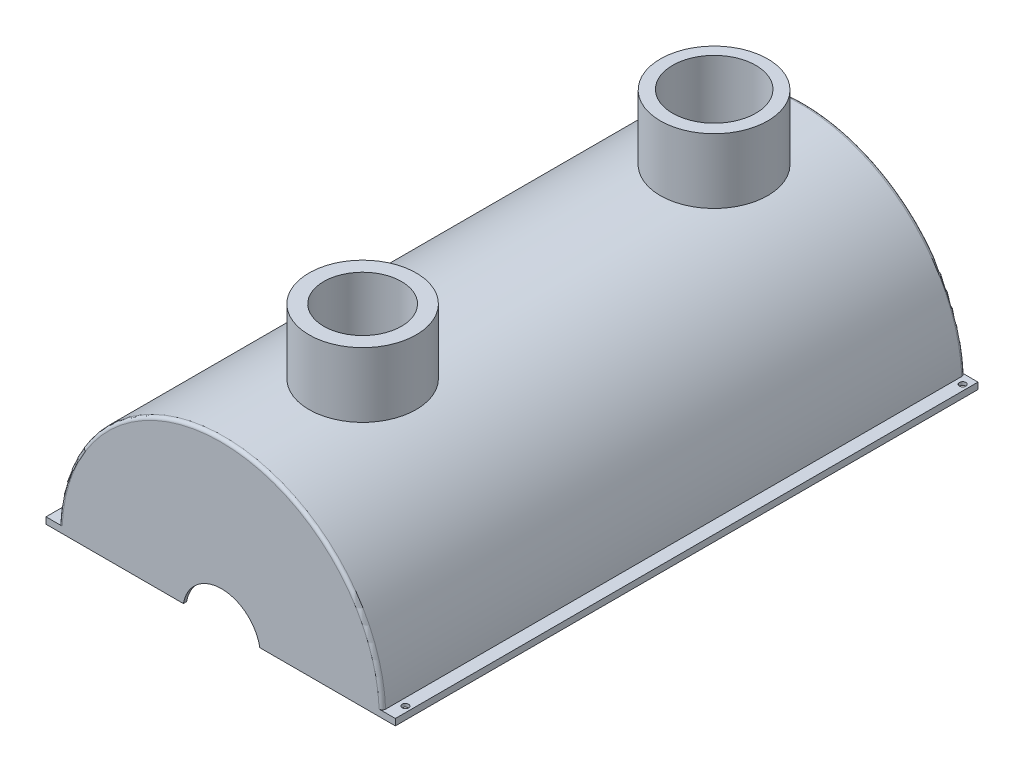
SolidWorks part; units mm, degrees
ref_plane "Front Plane" through (0, 0, 0) normal (0, 0, 1) x (1, 0, 0)
ref_plane "Top Plane" through (0, 0, 0) normal (0, 1, 0) x (1, 0, 0)
ref_plane "Right Plane" through (0, 0, 0) normal (1, 0, 0) x (0, 0, -1)
sketch "Sketch1" plane through (0, 0, 0) normal (0, 0, 1) x (1, 0, 0)
  line L0 (0, 0) -> (384.7575, 0)
  line L1 (620.9318, 0) -> (1000, 0)
  arc A0 (1000, 0) -> (0, 0) centre (500, 0) ccw
  arc A1 (384.7575, 0) -> (620.9318, 0) centre (502.8446, -21.3409) cw
  dimension "D2" = 120
  dimension "D1" = 1000
extrude "Boss-Extrude1" add sketch "Sketch1" along normal blind 1800
sketch "Sketch2" plane through (0, 0, 0) normal (0, 0, 1) x (1, 0, 0)
  line L0 (1000, 0) -> (1039.5998, 0)
  line L1 (1039.5998, 0) -> (1039.5998, 20)
  line L2 (1039.5998, 20) -> (999.5998, 20)
  line L3 (0, 0) -> (-39.5998, 0)
  line L4 (-39.5998, 0) -> (-39.5998, 20)
  line L5 (-39.5998, 20) -> (0.4002, 20)
  line L6 (999.5998, 20) -> (1000, 0)
  line L7 (0.4002, 20) -> (0, 0)
  arc A0 (1000, 0) -> (0, 0) centre (500, 0) ccw construction
extrude "Boss-Extrude2" add sketch "Sketch2" along normal blind 1800
shell "Shell1" thickness 10
fillet "Fillet1" radius 10 2 edges at (500, 500, 0) (500, 500, 1800)
sketch "Sketch3" plane through (0, 20, 0) normal (0, 1, 0) x (1, 0, 0)
  circle A0 centre (-18.2357, -19.6895) radius 10
  circle A1 centre (1021.8175, -29.6895) radius 10
  circle A2 centre (1021.8175, -1751.2087) radius 10
  circle A3 centre (-18.2357, -1741.2087) radius 10
extrude "Cut-Extrude1" cut sketch "Sketch3" against normal through all
ref_plane "Plane2" through (0, 500, 0) normal (0, 1, 0) x (1, 0, 0)
sketch "Sketch5" plane through (0, 500, 0) normal (0, 1, 0) x (1, 0, 0)
  circle A0 centre (530.2047, -305.9749) radius 165.9028
extrude "Boss-Extrude3" add sketch "Sketch5" along normal blind 200 separate body
sketch "Sketch6" plane through (0, 700, 0) normal (0, 1, 0) x (1, 0, 0)
  circle A0 centre (528.7951, -304.1626) radius 128.4705
extrude "Cut-Extrude2" cut sketch "Sketch6" against normal through all
ref_plane "Plane3" through (0, 500, 0) normal (0, 1, 0) x (1, 0, 0)
sketch "Sketch7" plane through (0, 500, 0) normal (0, 1, 0) x (1, 0, 0)
  circle A0 centre (559.9026, -1421.3749) radius 165.6
extrude "Boss-Extrude4" add sketch "Sketch7" along normal blind 200 separate body
sketch "Sketch8" plane through (0, 0, 0) normal (0, 1, 0) x (1, 0, 0)
  circle A0 centre (559.9026, -1421.3749) radius 120
extrude "Cut-Extrude5" cut sketch "Sketch8" along normal through all
